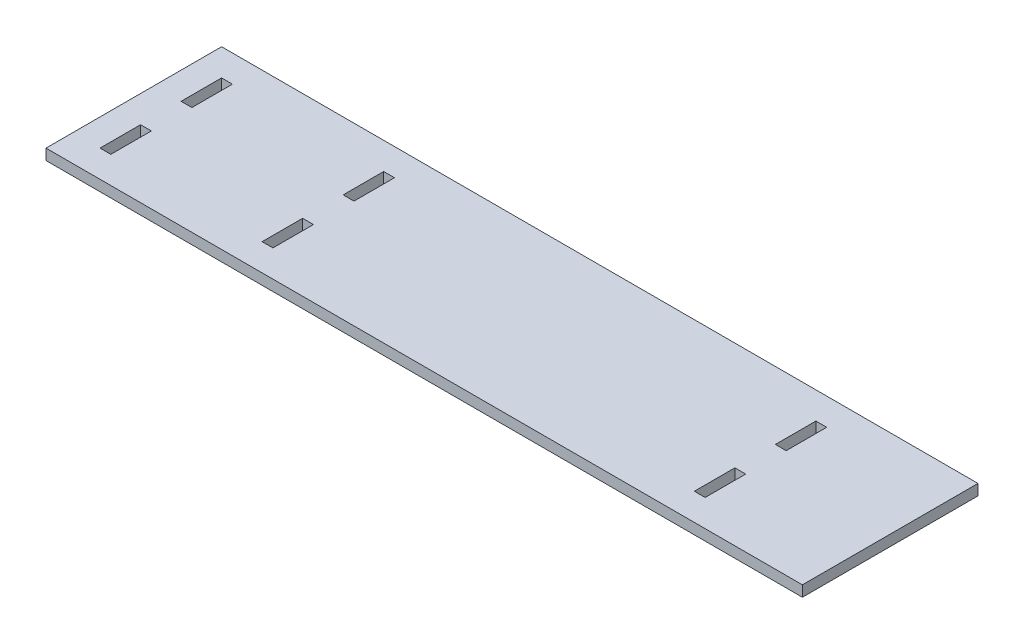
SolidWorks part; units mm, degrees
ref_plane "Front Plane" through (0, 0, 0) normal (0, 0, 1) x (1, 0, 0)
ref_plane "Top Plane" through (0, 0, 0) normal (0, 1, 0) x (1, 0, 0)
ref_plane "Right Plane" through (0, 0, 0) normal (1, 0, 0) x (0, 0, -1)
sketch "Sketch1" plane through (0, 0, 0) normal (0, 1, 0) x (1, 0, 0)
  line L1 (0, 0) -> (280, 0)
  line L2 (0, 0) -> (0, 65)
  line L3 (0, 65) -> (280, 65)
  line L4 (280, 0) -> (280, 65)
  dimension "D1" = 65
  dimension "D2" = 280
extrude "Boss-Extrude1" add sketch "Sketch1" along normal blind 4
sketch "Sketch2" plane through (0, 4, 0) normal (0, 1, 0) x (1, 0, 0)
  line L0 (0, 0) -> (280, 0) construction
  line L1 (74, 0) -> (70, 0)
  line L2 (74, 0) -> (74, 65)
  line L3 (74, 65) -> (70, 65)
  line L4 (70, 0) -> (70, 65)
  line L5 (280, 65) -> (0, 65) construction
  line L6 (0, 65) -> (0, 0) construction
  line L7 (14, 0) -> (14, 65)
  line L8 (70, 55) -> (74, 55)
  line L9 (70, 55) -> (70, 40)
  line L10 (70, 40) -> (74, 40)
  line L11 (74, 55) -> (74, 40)
  line L12 (74, 25) -> (70, 25)
  line L13 (74, 25) -> (74, 10)
  line L14 (74, 10) -> (70, 10)
  line L15 (70, 25) -> (70, 10)
  line L16 (14, 0) -> (10, 0)
  line L17 (10, 0) -> (10, 65)
  line L18 (14, 65) -> (10, 65)
  line L19 (10, 55) -> (10, 40)
  line L20 (10, 55) -> (14, 55)
  line L21 (14, 55) -> (14, 40)
  line L22 (10, 40) -> (14, 40)
  line L23 (14, 25) -> (14, 10)
  line L24 (14, 25) -> (10, 25)
  line L25 (10, 25) -> (10, 10)
  line L26 (14, 10) -> (10, 10)
  line L27 (230, 55) -> (230, 40)
  line L28 (230, 55) -> (234, 55)
  line L29 (234, 55) -> (234, 40)
  line L30 (230, 40) -> (234, 40)
  line L31 (234, 25) -> (234, 10)
  line L32 (234, 25) -> (230, 25)
  line L33 (230, 25) -> (230, 10)
  line L34 (234, 10) -> (230, 10)
  dimension "D1" = 4
  dimension "D2" = 70
  dimension "D3" = 15
  dimension "D4" = 15
  dimension "D5" = 10
  dimension "D6" = 10
  dimension "D7" = 2
extrude "Cut-Extrude1" cut sketch "Sketch2" against normal blind 4 contours L17 L22 L7 L20 | L26 L7 L24 L17 | L14 L2 L12 L4 | L4 L10 L2 L8 | L29 L30 L27 L28 | L31 L34 L33 L32
